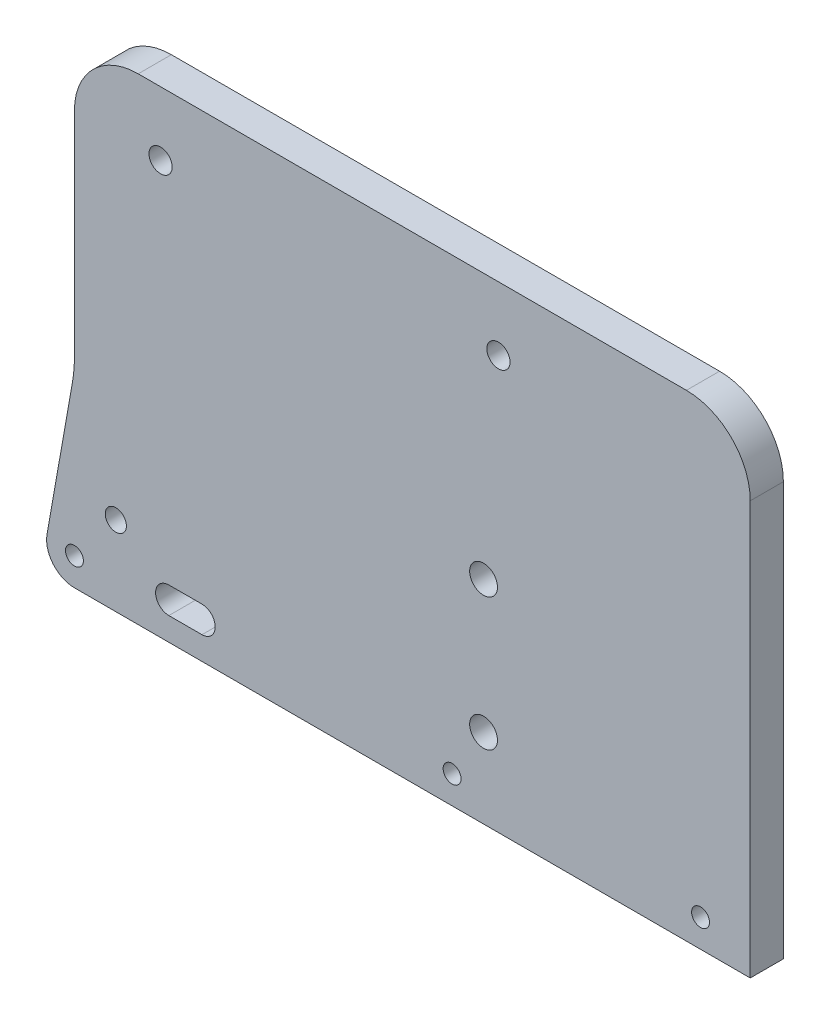
SolidWorks part; units mm, degrees
material "6061-T6 Black anodised"
ref_plane "Front Plane" through (0, 0, 0) normal (0, 0, 1) x (1, 0, 0)
ref_plane "Top Plane" through (0, 0, 0) normal (0, 1, 0) x (1, 0, 0)
ref_plane "Right Plane" through (0, 0, 0) normal (1, 0, 0) x (0, 0, -1)
sketch "Sketch1" plane through (0, 0, 0) normal (0, 0, 1) x (1, 0, 0)
  line L0 (-62.0538, 14.6636) -> (-65.8862, -7.0707)
  line L1 (0, 24.8959) -> (0, 0) construction
  line L2 (0, 0) -> (0, -5) construction
  line L3 (-61.75, -12) -> (40.25, -12)
  line L4 (-47.5, -6.5) -> (-42.5, -6.5) construction
  line L5 (-52.12, 60) -> (30.62, 60)
  line L6 (40.25, -12) -> (40.25, 50.37)
  line L7 (-47.5, -4.5) -> (-42.5, -4.5)
  line L8 (-61.75, 18.1366) -> (-61.75, 50.37)
  line L9 (-47.5, -8.5) -> (-42.5, -8.5)
  circle A0 centre (0, 0) radius 2.1
  arc A1 (-62.0538, 14.6636) -> (-61.75, 18.1366) centre (-81.75, 18.1366) ccw
  circle A2 centre (-48.75, 50.37) radius 1.75
  arc A3 (-65.8862, -7.0707) -> (-61.75, -12) centre (-61.75, -7.8) ccw
  circle A4 centre (32.75, -7.8) radius 1.35
  arc A5 (-52.12, 60) -> (-61.75, 50.37) centre (-52.12, 50.37) ccw
  arc A6 (40.25, 50.37) -> (30.62, 60) centre (30.62, 50.37) ccw
  arc A7 (-47.5, -4.5) -> (-47.5, -8.5) centre (-47.5, -6.5) ccw
  circle A8 centre (2.25, 50.37) radius 1.75
  arc A9 (-42.5, -8.5) -> (-42.5, -4.5) centre (-42.5, -6.5) ccw
  circle A10 centre (-61.75, -7.8) radius 1.35
  circle A11 centre (-4.75, -7.8) radius 1.35
  circle A12 centre (0, 20) radius 2.1
  circle A13 centre (-55.5, 0) radius 1.6
  point P28 (-45, -6.5)
  dimension "D1" = 3.5
  dimension "D2" = 48.75
  dimension "D3" = 7.8
  dimension "D4" = 51
  dimension "D5" = 4.75
  dimension "D6" = 57
  dimension "D7" = 37.5
  dimension "D13" = 20
  dimension "D14" = 2.7
  dimension "D15" = 4.2
  dimension "D19" = 2
  dimension "D22" = 3.2
  dimension "D23" = 55.5
  dimension "D8" = 20
  dimension "D9" = 50.37
  dimension "D10" = 102
  dimension "D11" = 61.75
  dimension "D12" = 12
  dimension "D16" = 10
  dimension "D17" = 60
  dimension "D18" = 5
  dimension "D20" = 5.5
  dimension "D21" = 45
extrude "Boss-Extrude1" add sketch "Sketch1" along normal blind 5
